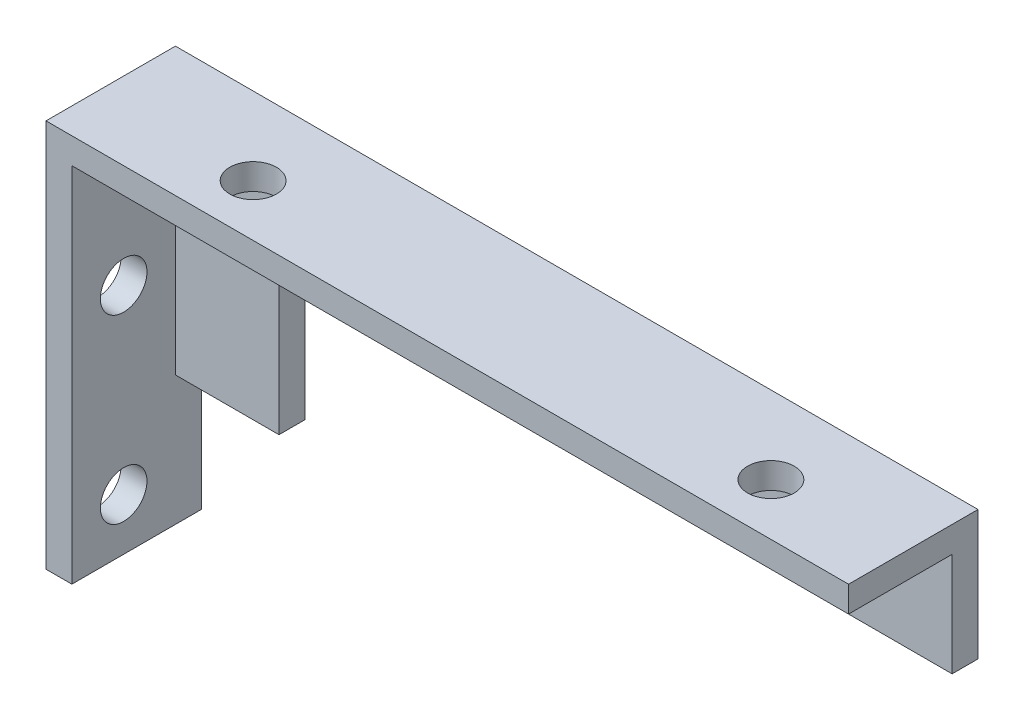
SolidWorks part; units mm, degrees
ref_plane "Plan de face" through (0, 0, 0) normal (0, 0, 1) x (1, 0, 0)
ref_plane "Plan de dessus" through (0, 0, 0) normal (0, 1, 0) x (1, 0, 0)
ref_plane "Plan de droite" through (0, 0, 0) normal (1, 0, 0) x (0, 0, -1)
sketch "Esquisse1" plane through (0, 0, 0) normal (0, 0, 1) x (1, 0, 0)
  line L0 (0, 0) -> (31, 0)
  line L1 (31, 0) -> (31, -5)
  line L2 (31, -5) -> (5, -5)
  line L3 (0, 0) -> (0, -15)
  line L4 (0, -15) -> (1, -15)
  line L5 (1, -15) -> (1, -10)
  line L6 (1, -10) -> (5, -10)
  line L7 (5, -10) -> (5, -5)
  dimension "D1" = 31
  dimension "D2" = 15
  dimension "D3" = 5
  dimension "D4" = 1
  dimension "D5" = 4
  dimension "D6" = 5
extrude "Boss.-Extru.1" add sketch "Esquisse1" along normal blind 5
sketch "Esquisse2" plane through (0, 0, 5) normal (0, 0, 1) x (1, 0, 0)
  line L0 (1, -10) -> (1, -1)
  line L1 (1, -1) -> (31, -1)
  line L2 (31, -5) -> (31, 0) construction
  line L3 (31, -1) -> (31, -5)
  line L4 (31, -5) -> (5, -5)
  line L5 (5, -5) -> (5, -10)
  line L6 (5, -10) -> (1, -10)
  dimension "D1" = 1
extrude "Enlèv. mat.-Extru.1" cut sketch "Esquisse2" against normal blind 4
sketch "Esquisse3" plane through (1, 0, 0) normal (1, 0, 0) x (0, 0, -1)
  line L0 (-1, -1) -> (-5, -1) construction
  line L1 (-5, -15) -> (-5, -1) construction
  circle A0 centre (-3, -6) radius 0.9
  circle A1 centre (-3, -13) radius 0.9
  point P9 (0, 0)
  dimension "D1" = 1.8
  dimension "D2" = 12
  dimension "D3" = 5
  dimension "D4" = 2
extrude "Enlèv. mat.-Extru.2" cut sketch "Esquisse3" against normal blind 10
sketch "Esquisse4" plane through (0, -1, 0) normal (0, -1, 0) x (1, 0, 0)
  line L1 (31, 5) -> (1, 5) construction
  circle A0 centre (6, 3) radius 0.9
  circle A1 centre (26, 3) radius 0.9
  point P4 (0, 0)
  point P6 (0, 0)
  point P8 (12.1163, 4.7302)
  dimension "D1" = 1.8
  dimension "D2" = 5
  dimension "D3" = 20
  dimension "D4" = 2
extrude "Enlèv. mat.-Extru.3" cut sketch "Esquisse4" against normal blind 10
